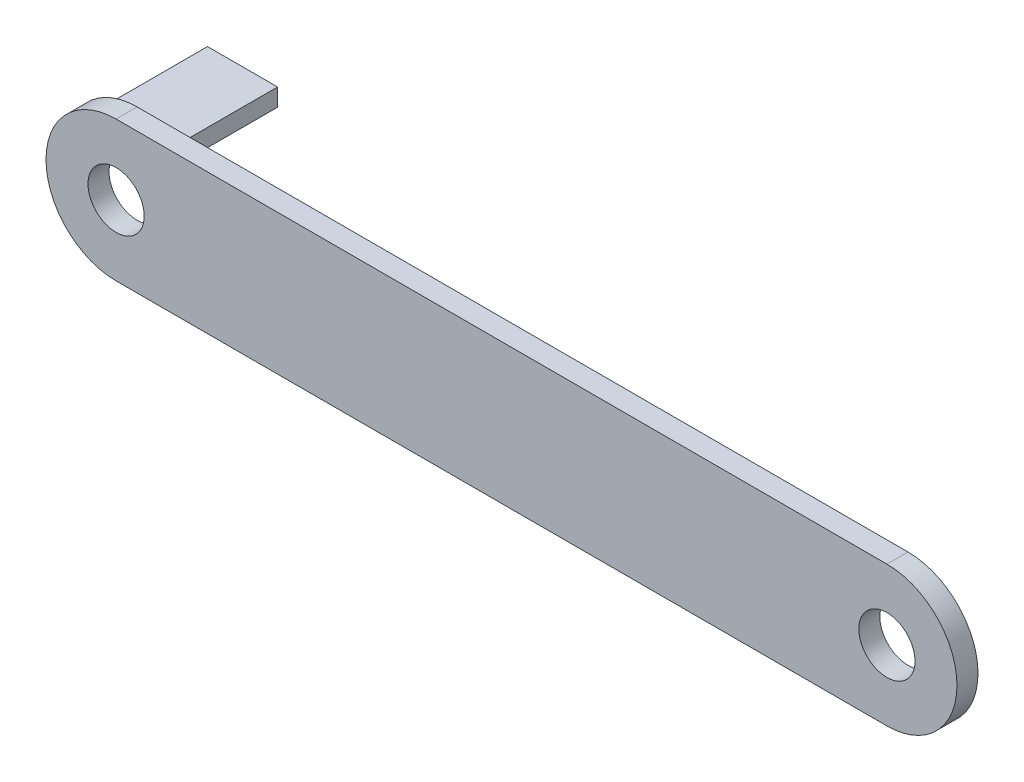
SolidWorks part; units mm, degrees
ref_plane "Front Plane" through (0, 0, 0) normal (0, 0, 1) x (1, 0, 0)
ref_plane "Top Plane" through (0, 0, 0) normal (0, 1, 0) x (1, 0, 0)
ref_plane "Right Plane" through (0, 0, 0) normal (1, 0, 0) x (0, 0, -1)
sketch "Sketch1" plane through (0, 0, 0) normal (0, 0, 1) x (1, 0, 0)
  line L0 (0, 10) -> (110, 10)
  line L1 (0, -10) -> (110, -10)
  circle A0 centre (0, 0) radius 10
  circle A2 centre (0, 0) radius 4.01
  circle A3 centre (110, 0) radius 4.01
  circle A4 centre (110, 0) radius 10
  dimension "D1" = 20
  dimension "D2" = 20
  dimension "D4" = 8.02
  dimension "D5" = 8.02
  dimension "D3" = 110
  dimension "D6" = 110
extrude "Boss-Extrude1" add sketch "Sketch1" along normal blind 3
sketch "Sketch2" plane through (0, 0, 0) normal (0, 0, -1) x (-1, 0, 0)
  circle A2 centre (-20, 0) radius 1.49
  dimension "D1" = 20
  dimension "D2" = 2.98
extrude "Boss-Extrude3" add sketch "Sketch2" along normal blind 4
sketch "Sketch4" plane through (0, 0, 0) normal (0, 0, -1) x (-1, 0, 0)
  line L0 (4.9531, 4.9852) -> (-5.0469, 4.9852)
  line L2 (4.9531, 4.9852) -> (-5.0469, 4.9852)
  line L3 (4.9531, 4.9852) -> (4.9531, 7.4852)
  line L4 (4.9531, 7.4852) -> (-5.0469, 7.4852)
  line L5 (-5.0469, 4.9852) -> (-5.0469, 7.4852)
  dimension "D1" = 2.5
  dimension "D2" = 10
extrude "Boss-Extrude5" add sketch "Sketch4" along normal blind 15 contours L5 L0 L3 L4
